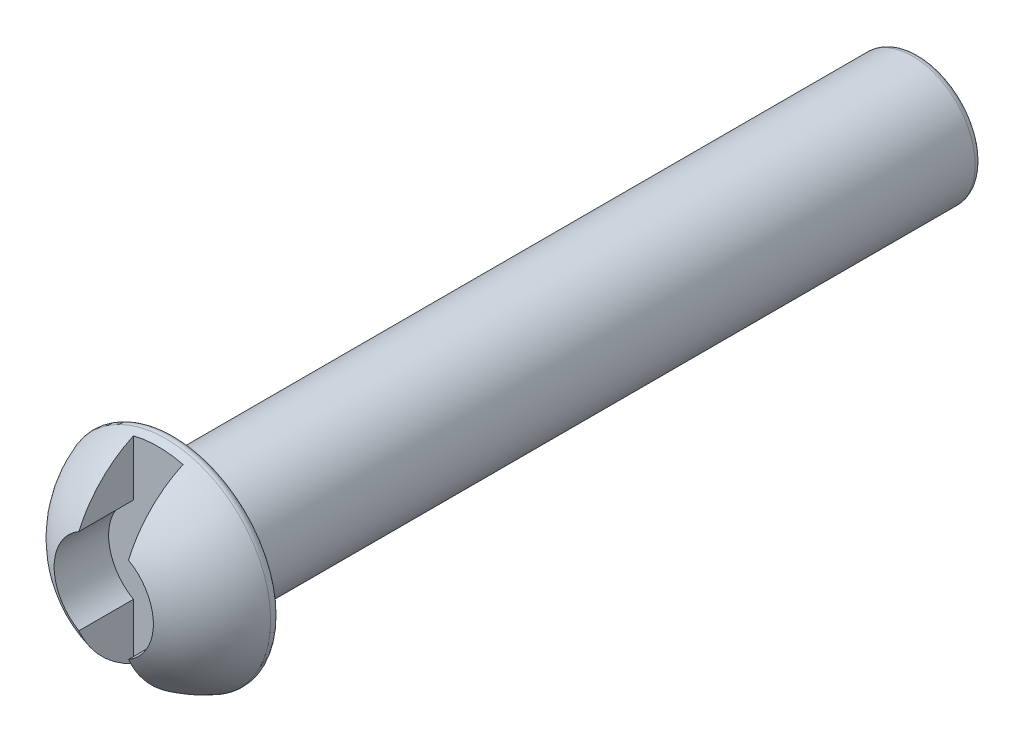
SolidWorks part; units mm, degrees
ref_plane "Front Plane" through (0, 0, 0) normal (0, 0, 1) x (1, 0, 0)
ref_plane "Top Plane" through (0, 0, 0) normal (0, 1, 0) x (1, 0, 0)
ref_plane "Right Plane" through (0, 0, 0) normal (1, 0, 0) x (0, 0, -1)
sketch "Sketch2" plane through (0, 0, 0) normal (1, 0, 0) x (0, 0, -1)
  line L0 (0, 0) -> (12.5, 0)
  line L1 (12.5, 0) -> (12.5, 0.95)
  line L2 (12.5, 0.95) -> (1.25, 0.95)
  line L3 (1.25, 0.95) -> (1.25, 1.625)
  arc A0 (0, 0) -> (1.25, 1.625) centre (1.6812, 0) cw
  dimension "D1" = 12.5
  dimension "D2" = 0.95
  dimension "D3" = 1.625
  dimension "D4" = 1.25
revolve "Revolve1" add sketch "Sketch2" angle 360 about L0
sketch "Sketch3" plane through (0, 0, 0) normal (0, 0, 1) x (1, 0, 0)
  line L0 (0.375, 0.6495) -> (0.375, 2.0468)
  line L1 (-0.375, -2.0468) -> (0.375, -2.0468)
  line L2 (-0.375, -2.0468) -> (-0.375, -0.6495)
  line L3 (-0.375, 2.0468) -> (0.375, 2.0468)
  line L4 (0.375, -2.0468) -> (0.375, -0.6495)
  line L7 (0.1352, 0.7377) -> (0.375, 2.0468) construction
  line L8 (0.1352, -0.7377) -> (0.375, -2.0468) construction
  line L9 (-0.375, 0.6495) -> (-0.375, 2.0468)
  arc A0 (-0.375, 0.6495) -> (-0.375, -0.6495) centre (0, 0) ccw
  arc A1 (0.375, -0.6495) -> (0.375, 0.6495) centre (0, 0) ccw
  point P0 (0, 0)
  dimension "D2" = 1.5
  dimension "D1" = 0.75
extrude "Cut-Extrude1" cut sketch "Sketch3" against normal blind 1
fillet "Fillet1" radius 0.1 2 edges at (0.95, 0, -12.5) (1.625, 0, -1.25)
